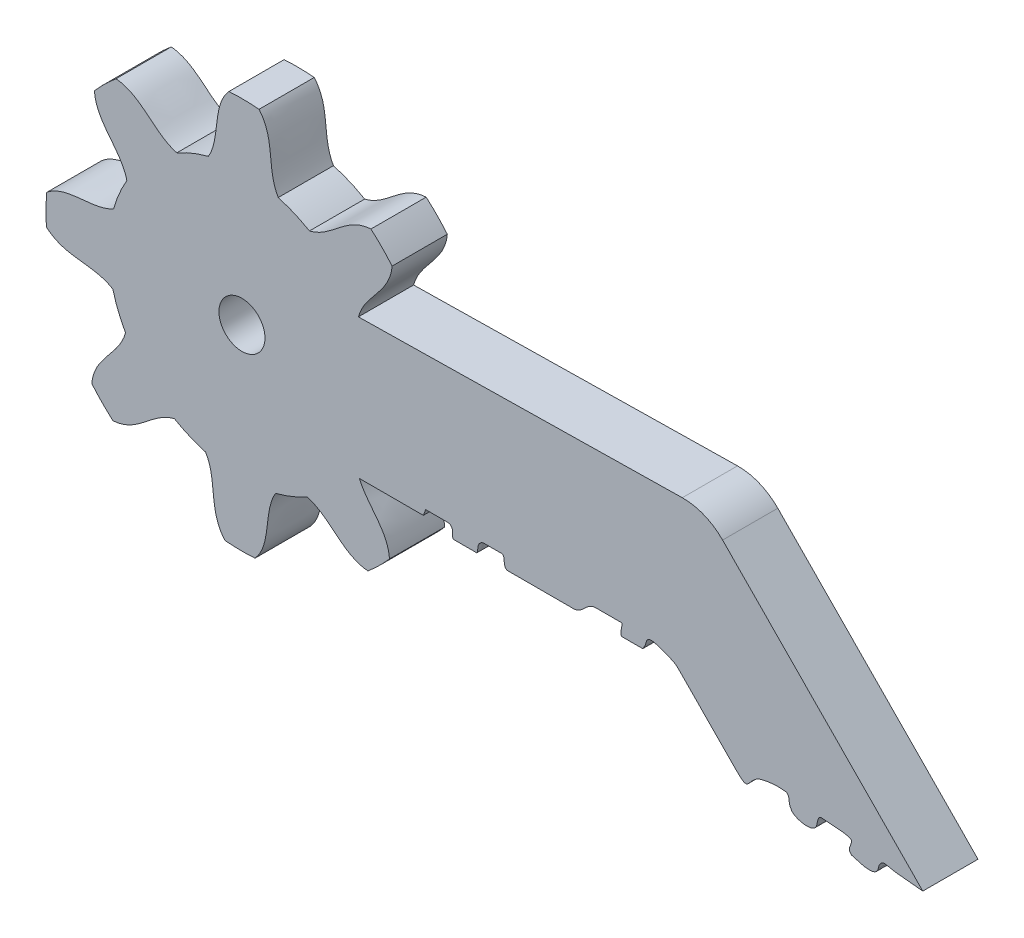
SolidWorks part; units mm, degrees
ref_plane "Plan de face" through (0, 0, 0) normal (0, 0, 1) x (1, 0, 0)
ref_plane "Plan de dessus" through (0, 0, 0) normal (0, 1, 0) x (1, 0, 0)
ref_plane "Plan de droite" through (0, 0, 0) normal (1, 0, 0) x (0, 0, -1)
sketch "Esquisse1" plane through (0, 0, 0) normal (0, 0, 1) x (1, 0, 0)
  line L0 (-3.7346, -4.4852) -> (-2.7697, -4.4852)
  line L1 (-2.208, -5.1322) -> (-0.9759, -5.1322)
  line L2 (-0.5406, -4.4852) -> (0.3933, -4.4852)
  line L3 (0.7603, -5.1322) -> (4.2916, -5.1322)
  line L4 (5.5036, -4.4852) -> (6.8775, -4.4852)
  line L5 (6.9587, -5.1322) -> (8.0605, -5.1322)
  line L6 (10.0113, -5.1243) -> (13.0647, -8.2341)
  line L7 (21.9111, -8.7971) -> (23.2798, -8.9322)
  line L8 (23.2798, -8.9322) -> (11.4978, 3.0678)
  line L9 (11.4978, 3.0678) -> (-3.7904, 3.0678) construction
  line L10 (-24.1662, -1.2157) -> (22.8338, -1.2157) construction
  line L11 (11.4978, 3.0678) -> (-7.3926, 2.7568)
  line L12 (-3.7346, -4.4852) -> (-3.8652, -4.8199)
  line L13 (-7.3421, -4.8199) -> (-3.8652, -4.8199)
  circle A0 centre (-13.7202, -0.7822) radius 1.25
  arc A1 (-3.7904, 3.0678) -> (-4.2166, 4.0245) centre (-13.7202, -0.7822) ccw construction
  arc A2 (-7.9762, 3.6416) -> (-9.2784, 4.9478) centre (-13.7202, -0.7822) ccw construction
  arc A3 (-8.8838, 8.7063) -> (-10.399, 9.3367) centre (-13.7202, -0.7822) ccw construction
  arc A4 (-12.7867, 6.4074) -> (-14.6311, 6.4103) centre (-13.7202, -0.7822) ccw construction
  arc A5 (-17.0097, 9.347) -> (-18.5269, 8.7213) centre (-13.7202, -0.7822) ccw construction
  arc A6 (-18.144, 4.9617) -> (-19.4502, 3.6595) centre (-13.7202, -0.7822) ccw construction
  arc A7 (-23.2087, 4.0541) -> (-23.8391, 2.5389) centre (-13.7202, -0.7822) ccw construction
  arc A8 (-20.9098, 0.1512) -> (-20.9127, -1.6932) centre (-13.7202, -0.7822) ccw construction
  arc A9 (-23.8494, -4.0718) -> (-23.2237, -5.589) centre (-13.7202, -0.7822) ccw construction
  arc A10 (-19.4641, -5.2061) -> (-18.1619, -6.5123) centre (-13.7202, -0.7822) ccw construction
  arc A11 (-18.5565, -10.2708) -> (-17.0413, -10.9012) centre (-13.7202, -0.7822) ccw construction
  arc A12 (-14.6536, -7.9719) -> (-12.8092, -7.9748) centre (-13.7202, -0.7822) ccw construction
  arc A13 (-10.4306, -10.9115) -> (-8.9134, -10.2858) centre (-13.7202, -0.7822) ccw construction
  arc A14 (-9.2963, -6.5261) -> (-7.9901, -5.224) centre (-13.7202, -0.7822) ccw construction
  arc A15 (-4.2316, -5.6186) -> (-3.7346, -4.4852) centre (-13.7202, -0.7822) ccw construction
  arc A16 (8.0605, -5.1322) -> (8.2721, -4.666) centre (6.8879, -4.3188) ccw
  arc A17 (15.8619, -7.9748) -> (14.5104, -8.0665) centre (15.4216, -11.4901) ccw
  circle A18 centre (-13.7202, -0.7822) radius 7.25 construction
  arc A19 (-6.8756, -8.9416) -> (-5.7033, -7.7932) centre (-13.7202, -0.7822) ccw
  arc A20 (-14.6499, -11.3916) -> (-13.0089, -11.4085) centre (-13.7202, -0.7822) ccw
  arc A21 (-21.8795, -7.6267) -> (-20.7311, -8.7991) centre (-13.7202, -0.7822) ccw
  arc A22 (-24.3295, 0.1475) -> (-24.3464, -1.4935) centre (-13.7202, -0.7822) ccw
  arc A23 (-20.5647, 7.3771) -> (-21.737, 6.2287) centre (-13.7202, -0.7822) ccw
  arc A24 (-12.7904, 9.8271) -> (-14.4314, 9.844) centre (-13.7202, -0.7822) ccw
  arc A25 (-5.5608, 6.0623) -> (-6.7092, 7.2346) centre (-13.7202, -0.7822) ccw
  arc A26 (-10.0517, 5.4711) -> (-11.7484, 6.1945) centre (-13.7202, -0.7822) ccw
  arc A27 (-3.1108, -1.712) -> (-3.0939, -0.071) centre (-13.7202, -0.7822) ccw [skipped]
  arc A28 (-10.1811, -7.1098) -> (-11.8923, -7.7981) centre (-13.7202, -0.7822) cw
  arc A29 (-15.6919, -7.759) -> (-17.3886, -7.0356) centre (-13.7202, -0.7822) cw
  arc A30 (-20.0477, -4.3213) -> (-20.736, -2.6101) centre (-13.7202, -0.7822) cw
  arc A31 (-20.6969, 1.1895) -> (-19.9735, 2.8862) centre (-13.7202, -0.7822) cw
  arc A32 (-17.2592, 5.5453) -> (-15.548, 6.2336) centre (-13.7202, -0.7822) cw
  spline S0 degree 3 poles (-4.2166, 4.0245) (-5.5482, 4.4683) (-6.6895, 3.4541) (-7.9762, 3.6416) knots 0 0 0 0 1 1 1 1 construction
  spline S1 degree 3 poles (-9.2784, 4.9478) (-9.4619, 6.2351) (-8.4441, 7.3733) (-8.8838, 8.7063) knots 0 0 0 0 1 1 1 1 construction
  spline S2 degree 3 poles (-10.399, 9.3367) (-11.6544, 8.7089) (-11.7443, 7.1847) (-12.7867, 6.4074) knots 0 0 0 0 1 1 1 1 construction
  spline S3 degree 3 poles (-14.6311, 6.4103) (-15.6711, 7.1908) (-15.7563, 8.7153) (-17.0097, 9.347) knots 0 0 0 0 1 1 1 1 construction
  spline S4 degree 3 poles (-18.5269, 8.7213) (-18.9707, 7.3897) (-17.9565, 6.2484) (-18.144, 4.9617) knots 0 0 0 0 1 1 1 1 construction
  spline S5 degree 3 poles (-19.4502, 3.6595) (-20.7375, 3.476) (-21.8757, 4.4938) (-23.2087, 4.0541) knots 0 0 0 0 1 1 1 1 construction
  spline S6 degree 3 poles (-23.8391, 2.5389) (-23.2113, 1.2835) (-21.6871, 1.1936) (-20.9098, 0.1512) knots 0 0 0 0 1 1 1 1 construction
  spline S7 degree 3 poles (-20.9127, -1.6932) (-21.6932, -2.7332) (-23.2177, -2.8184) (-23.8494, -4.0718) knots 0 0 0 0 1 1 1 1 construction
  spline S8 degree 3 poles (-23.2237, -5.589) (-21.8921, -6.0328) (-20.7508, -5.0186) (-19.4641, -5.2061) knots 0 0 0 0 1 1 1 1 construction
  spline S9 degree 3 poles (-18.1619, -6.5123) (-17.9784, -7.7996) (-18.9962, -8.9378) (-18.5565, -10.2708) knots 0 0 0 0 1 1 1 1 construction
  spline S10 degree 3 poles (-17.0413, -10.9012) (-15.7859, -10.2734) (-15.696, -8.7492) (-14.6536, -7.9719) knots 0 0 0 0 1 1 1 1 construction
  spline S11 degree 3 poles (-12.8092, -7.9748) (-11.7692, -8.7553) (-11.684, -10.2798) (-10.4306, -10.9115) knots 0 0 0 0 1 1 1 1 construction
  spline S12 degree 3 poles (-8.9134, -10.2858) (-8.4696, -8.9542) (-9.4838, -7.8129) (-9.2963, -6.5261) knots 0 0 0 0 1 1 1 1 construction
  spline S13 degree 3 poles (-7.9901, -5.224) (-6.6905, -4.6986) (-5.6268, -6.4419) (-4.2316, -5.6186) knots 0 0 0 0 1 1 1 1 construction
  spline S14 degree 3 poles (-2.7697, -4.4852) (-2.5771, -4.4852) (-2.3317, -4.4686) (-2.2487, -4.8076) (-2.2777, -5.1322) (-2.208, -5.1322) knots 0 0 0 0 0.517237 0.84797 1 1 1 1
  spline S15 degree 3 poles (-0.9759, -5.1322) (-0.8971, -5.1322) (-0.9496, -4.6988) (-0.728, -4.4852) (-0.5406, -4.4852) knots 0 0 0 0 0.38685 1 1 1 1
  spline S16 degree 3 poles (0.3933, -4.4852) (0.6389, -4.4852) (0.399, -5.1433) (0.7603, -5.1322) knots 0 0 0 0 0.869022 0.869022 0.869022 0.869022
  spline S17 degree 3 poles (4.2916, -5.1322) (4.8238, -5.1322) (4.9763, -4.4852) (5.5036, -4.4852) knots 0 0 0 0 1 1 1 1
  spline S18 degree 3 poles (6.8775, -4.4852) (6.9766, -4.4852) (6.8708, -4.8172) (6.8467, -5.1322) (6.9587, -5.1322) knots 0 0 0 0 0.526016 1 1 1 1
  spline S19 degree 3 poles (8.2721, -4.666) (8.3492, -4.3587) (9.3371, -4.7628) (9.7943, -4.9032) (10.0113, -5.1243) knots 0 0 0 0 0.527261 1 1 1 1
  spline S20 degree 3 poles (13.0647, -8.2341) (13.4903, -8.6676) (13.7856, -8.8274) (14.0751, -8.1824) (14.5104, -8.0665) knots 0 0 0 0 0.460711 1 1 1 1
  spline S21 degree 3 poles (15.8619, -7.9748) (16.1016, -8.1542) (15.9352, -8.3959) (16.1241, -8.644) knots 0 0 0 0 1 1 1 1
  spline S22 degree 3 poles (16.1241, -8.644) (16.1845, -8.9461) (17.7065, -9.3506) (17.5234, -8.3054) (17.7464, -8.2341) knots 0 0 0 0 0.70566 1 1 1 1
  spline S23 degree 3 poles (17.7464, -8.2341) (17.7839, -8.2222) (18.7856, -8.3261) (19.0794, -8.3212) (19.358, -8.4454) knots 0 0 0 0 0.477701 1 1 1 1
  spline S24 degree 3 poles (19.358, -8.4454) (19.5129, -8.5145) (19.1487, -8.9514) (19.3673, -9.1244) (19.427, -9.1832) knots 0 0 0 0 0.680949 1 1 1 1
  spline S25 degree 3 poles (19.427, -9.1832) (19.3774, -9.1343) (20.0107, -9.4205) (20.7871, -9.4222) (20.8546, -9.0853) knots 0 0 0 0 0.494583 1 1 1 1
  spline S26 degree 3 poles (20.8546, -9.0853) (20.8897, -8.9103) (21.0904, -8.529) (21.4851, -8.7551) (21.9111, -8.7971) knots 0 0 0 0 0.363922 1 1 1 1
  spline S27 degree 3 poles (-10.1811, -7.1098) (-8.9245, -7.4439) (-8.2744, -8.8255) (-6.8756, -8.9416) knots 0 0 0 0 1 1 1 1
  spline S28 degree 3 poles (-5.7033, -7.7932) (-5.7818, -6.535) (-6.8932, -5.8596) (-7.3421, -4.8199) knots 0 0 0 0 0.898148 0.898148 0.898148 0.898148
  spline S29 degree 3 poles (-15.6919, -7.759) (-15.0396, -8.8838) (-15.5569, -10.3204) (-14.6499, -11.3916) knots 0 0 0 0 1 1 1 1
  spline S30 degree 3 poles (-13.0089, -11.4085) (-12.08, -10.3562) (-12.5677, -8.9092) (-11.8923, -7.7981) knots 0 0 0 0 1 1 1 1
  spline S31 degree 3 poles (-20.0477, -4.3213) (-20.3818, -5.5779) (-21.7634, -6.2279) (-21.8795, -7.6267) knots 0 0 0 0 1 1 1 1
  spline S32 degree 3 poles (-20.7311, -8.7991) (-19.3302, -8.7117) (-18.6519, -7.3438) (-17.3886, -7.0356) knots 0 0 0 0 1 1 1 1
  spline S33 degree 3 poles (-20.6969, 1.1895) (-21.8217, 0.5372) (-23.2583, 1.0545) (-24.3295, 0.1475) knots 0 0 0 0 1 1 1 1
  spline S34 degree 3 poles (-24.3464, -1.4935) (-23.2941, -2.4223) (-21.8471, -1.9347) (-20.736, -2.6101) knots 0 0 0 0 1 1 1 1
  spline S35 degree 3 poles (-17.2592, 5.5453) (-18.5158, 5.8794) (-19.1659, 7.261) (-20.5647, 7.3771) knots 0 0 0 0 1 1 1 1
  spline S36 degree 3 poles (-21.737, 6.2287) (-21.6497, 4.8278) (-20.2817, 4.1495) (-19.9735, 2.8862) knots 0 0 0 0 1 1 1 1
  spline S37 degree 3 poles (-11.7484, 6.1945) (-12.4007, 7.3193) (-11.8834, 8.7559) (-12.7904, 9.8271) knots 0 0 0 0 1 1 1 1
  spline S38 degree 3 poles (-14.4314, 9.844) (-15.3603, 8.7917) (-14.8726, 7.3447) (-15.548, 6.2336) knots 0 0 0 0 1 1 1 1
  spline S39 degree 3 poles (-7.3926, 2.7568) (-7.0585, 4.0134) (-5.6769, 4.6635) (-5.5608, 6.0623) knots 0 0 0 0 1 1 1 1
  spline S40 degree 3 poles (-6.7092, 7.2346) (-8.1101, 7.1473) (-8.7884, 5.7793) (-10.0517, 5.4711) knots 0 0 0 0 1 1 1 1
  point P81 (-13.7202, -0.7822)
  point P111 (-13.7202, -0.7822)
  dimension "D2" = 2
  dimension "D1" = 47
  dimension "D3" = 8
extrude "Boss.-Extru.1" add sketch "Esquisse1" along normal blind 3
fillet "Congé1" radius 3 1 edges at (11.4978, 3.0678, 1.5)
